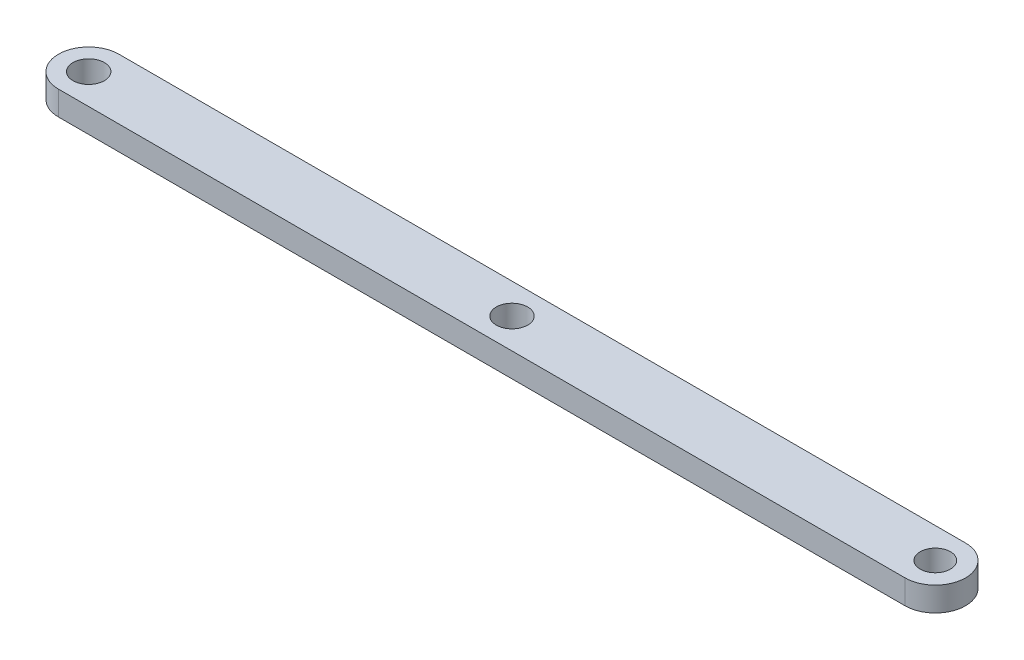
SolidWorks part; units mm, degrees
material "ABS"
ref_plane "Front Plane" through (0, 0, 0) normal (0, 0, 1) x (1, 0, 0)
ref_plane "Top Plane" through (0, 0, 0) normal (0, 1, 0) x (1, 0, 0)
ref_plane "Right Plane" through (0, 0, 0) normal (1, 0, 0) x (0, 0, -1)
sketch "Sketch1" plane through (0, 0, 0) normal (0, 1, 0) x (1, 0, 0)
  line L1 (-61.1673, -4.2117) -> (27.7327, -4.2117)
  line L2 (-61.1673, -4.2117) -> (-61.1673, -10.5617)
  line L3 (-61.1673, -10.5617) -> (27.7327, -10.5617)
  line L4 (27.7327, -4.2117) -> (27.7327, -10.5617)
  circle A0 centre (-61.1673, -7.3867) radius 3.175
  circle A1 centre (27.7327, -7.3867) radius 3.175
  dimension "D1" = 6.35
  dimension "D2" = 88.9
extrude "Boss-Extrude1" add sketch "Sketch1" along normal blind 2.54 contours L2 A0 | A1 L1 A0 L3 | L4 A1 | L4 A1 | L2 A0
sketch "Sketch2" plane through (0, 2.54, 0) normal (0, 1, 0) x (1, 0, 0)
  circle A0 centre (-61.1673, -7.3867) radius 1.651
  circle A1 centre (27.7327, -7.3867) radius 1.5875
  dimension "D1" = 3.302
  dimension "D2" = 3.175
extrude "Cut-Extrude1" cut sketch "Sketch2" against normal blind 2.54
sketch "Sketch3" plane through (0, 2.54, 0) normal (0, 1, 0) x (1, 0, 0)
  line L0 (-61.1673, -4.2117) -> (27.7327, -4.2117) construction
  circle A0 centre (-16.7173, -7.3867) radius 1.651
  arc A1 (27.7327, -10.5617) -> (27.7327, -4.2117) centre (27.7327, -7.3867) ccw construction
  dimension "D1" = 3.302
  dimension "D2" = 3.175
  dimension "D3" = 44.45
extrude "Cut-Extrude2" cut sketch "Sketch3" against normal blind 2.54
